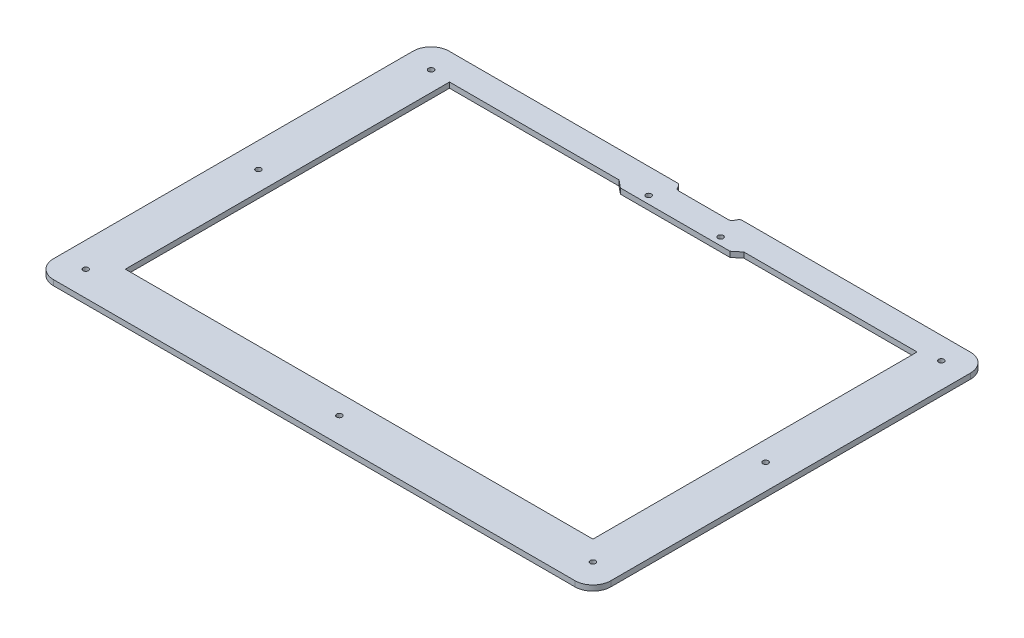
SolidWorks part; units mm, degrees
ref_plane "前视基准面" through (0, 0, 0) normal (0, 0, 1) x (1, 0, 0)
ref_plane "上视基准面" through (0, 0, 0) normal (0, 1, 0) x (1, 0, 0)
ref_plane "右视基准面" through (0, 0, 0) normal (1, 0, 0) x (0, 0, -1)
sketch "草图1" plane through (0, 0, 0) normal (0, 1, 0) x (1, 0, 0)
  line L0 (184.4552, -18.25) -> (188.75, -14.75)
  line L1 (10, 0) -> (136.8844, 0)
  line L2 (0, -10) -> (0, -210)
  line L3 (10, -220) -> (300, -220)
  line L4 (310, -10) -> (310, -210)
  line L5 (28.75, -14.75) -> (47.25, -14.75) construction
  line L6 (28.75, -14.75) -> (28.75, -33.25) construction
  line L7 (28.75, -33.25) -> (47.25, -33.25) construction
  line L8 (173, -85) -> (173, 0) construction
  line L9 (173, -85) -> (310, -85) construction
  line L10 (190, -66) -> (190, 0) construction
  line L11 (215, -58) -> (215, 0) construction
  line L12 (241, -58) -> (241, 0) construction
  line L13 (247, -84) -> (247, 0) construction
  line L14 (222, -84) -> (222, 0) construction
  line L15 (0, -220) -> (310, 0) construction
  line L16 (241, -58) -> (310, -58) construction
  line L17 (247, -84) -> (310, -84) construction
  line L18 (215, -58) -> (310, -58) construction
  line L19 (222, -84) -> (310, -84) construction
  line L20 (190, -66) -> (310, -66) construction
  line L21 (310, -220) -> (0, 0) construction
  line L23 (139.4291, -2.4682) -> (138.6344, -1.0318)
  line L24 (170.5709, -2.4682) -> (171.3656, -1.0318)
  line L25 (173.1156, 0) -> (300, 0)
  line L26 (155, -110) -> (155, -220) construction
  line L27 (47.25, -14.75) -> (47.25, -33.25) construction
  line L28 (28.75, -14.75) -> (47.25, -33.25) construction
  line L29 (28.75, -33.25) -> (47.25, -14.75) construction
  line L30 (52.75, -14.75) -> (71.25, -14.75) construction
  line L31 (52.75, -14.75) -> (52.75, -33.25) construction
  line L32 (52.75, -33.25) -> (71.25, -33.25) construction
  line L33 (71.25, -14.75) -> (71.25, -33.25) construction
  line L34 (52.75, -14.75) -> (71.25, -33.25) construction
  line L35 (52.75, -33.25) -> (71.25, -14.75) construction
  line L36 (76.75, -14.75) -> (95.25, -14.75) construction
  line L37 (76.75, -14.75) -> (76.75, -33.25) construction
  line L38 (76.75, -33.25) -> (95.25, -33.25) construction
  line L39 (95.25, -14.75) -> (95.25, -33.25) construction
  line L40 (76.75, -14.75) -> (95.25, -33.25) construction
  line L41 (76.75, -33.25) -> (95.25, -14.75) construction
  line L42 (100.75, -14.75) -> (119.25, -14.75) construction
  line L43 (100.75, -14.75) -> (100.75, -33.25) construction
  line L44 (100.75, -33.25) -> (119.25, -33.25) construction
  line L45 (119.25, -14.75) -> (119.25, -33.25) construction
  line L46 (100.75, -14.75) -> (119.25, -33.25) construction
  line L47 (100.75, -33.25) -> (119.25, -14.75) construction
  line L48 (188.75, -14.75) -> (207.25, -14.75) construction
  line L49 (188.75, -14.75) -> (188.75, -33.25) construction
  line L50 (188.75, -33.25) -> (207.25, -33.25) construction
  line L51 (207.25, -14.75) -> (207.25, -33.25) construction
  line L52 (188.75, -14.75) -> (207.25, -33.25) construction
  line L53 (188.75, -33.25) -> (207.25, -14.75) construction
  line L54 (212.75, -14.75) -> (231.25, -14.75) construction
  line L55 (212.75, -14.75) -> (212.75, -33.25) construction
  line L56 (212.75, -33.25) -> (231.25, -33.25) construction
  line L57 (231.25, -14.75) -> (231.25, -33.25) construction
  line L58 (212.75, -14.75) -> (231.25, -33.25) construction
  line L59 (212.75, -33.25) -> (231.25, -14.75) construction
  line L60 (236.75, -14.75) -> (255.25, -14.75) construction
  line L61 (236.75, -14.75) -> (236.75, -33.25) construction
  line L62 (236.75, -33.25) -> (255.25, -33.25) construction
  line L63 (255.25, -14.75) -> (255.25, -33.25) construction
  line L64 (236.75, -14.75) -> (255.25, -33.25) construction
  line L65 (236.75, -33.25) -> (255.25, -14.75) construction
  line L66 (260.75, -14.75) -> (279.25, -14.75) construction
  line L67 (260.75, -14.75) -> (260.75, -33.25) construction
  line L68 (260.75, -33.25) -> (279.25, -33.25) construction
  line L69 (279.25, -14.75) -> (279.25, -33.25) construction
  line L70 (260.75, -14.75) -> (279.25, -33.25) construction
  line L71 (260.75, -33.25) -> (279.25, -14.75) construction
  line L73 (123.5448, -18.25) -> (141.1791, -18.25)
  line L74 (141.1791, -18.25) -> (141.1791, -3.5) construction
  line L75 (119.25, -14.75) -> (25, -14.75)
  line L76 (25, -14.75) -> (25, -195)
  line L77 (25, -195) -> (285, -195)
  line L79 (285, -195) -> (285, -14.75)
  line L80 (188.75, -14.75) -> (285, -14.75)
  line L81 (184.4552, -18.25) -> (168.8209, -18.25)
  line L82 (168.8209, -3.5) -> (168.8209, -18.25) construction
  line L83 (123.5448, -18.25) -> (119.25, -14.75)
  line L84 (141.1791, -3.5) -> (168.8209, -3.5)
  line L85 (141.1791, -18.25) -> (168.8209, -18.25)
  arc A0 (10, 0) -> (0, -10) centre (10, -10) ccw
  arc A1 (0, -210) -> (10, -220) centre (10, -210) ccw
  arc A2 (300, -220) -> (310, -210) centre (300, -210) ccw
  arc A3 (300, 0) -> (310, -10) centre (300, -10) cw
  circle A8 centre (173, -85) radius 11 construction
  circle A9 centre (190, -66) radius 11 construction
  circle A11 centre (215, -58) radius 11 construction
  circle A12 centre (222, -84) radius 11 construction
  circle A13 centre (247, -84) radius 11 construction
  circle A14 centre (241, -58) radius 11 construction
  circle A15 centre (14, -14) radius 1.5
  circle A16 centre (14, -206) radius 1.5
  circle A17 centre (296, -206) radius 1.5
  circle A18 centre (296, -12.2857) radius 1.5
  arc A19 (173.1156, 0) -> (171.3656, -1.0318) centre (173.1156, -2) ccw
  arc A20 (170.5709, -2.4682) -> (168.8209, -3.5) centre (168.8209, -1.5) cw
  arc A21 (141.1791, -3.5) -> (139.4291, -2.4682) centre (141.1791, -1.5) cw
  arc A22 (136.8844, 0) -> (138.6344, -1.0318) centre (136.8844, -2) cw
  circle A24 centre (198, -90) radius 11 construction
  circle A25 centre (114, -130) radius 13.5 construction
  circle A26 centre (190, -130) radius 13.5 construction
  circle A27 centre (155, -206) radius 1.5
  circle A28 centre (175, -14) radius 1.5
  circle A29 centre (145, -138) radius 11 construction
  circle A30 centre (106, -90) radius 11 construction
  circle A31 centre (84, -77) radius 11 construction
  circle A32 centre (58, -80) radius 11 construction
  circle A33 centre (36, -97) radius 11 construction
  circle A34 centre (89, -53) radius 11 construction
  circle A35 centre (266, -66) radius 11 construction
  circle A36 centre (110, -24) radius 4.5 construction
  circle A37 centre (86, -24) radius 4.5 construction
  circle A38 centre (62, -24) radius 4.5 construction
  circle A39 centre (38, -24) radius 4.5 construction
  circle A40 centre (198, -24) radius 4.5 construction
  circle A41 centre (222, -24) radius 4.5 construction
  circle A42 centre (246, -24) radius 4.5 construction
  circle A43 centre (270, -24) radius 4.5 construction
  circle A48 centre (135, -14) radius 1.5
  circle A51 centre (296, -110) radius 1.5
  circle A52 centre (14, -110) radius 1.5
  point P8 (0, 0)
  point P12 (0, -220)
  point P15 (310, -220)
  point P18 (310, 0)
  point P70 (171.9365, 0)
  point P73 (170, -3.5)
  point P76 (140, -3.5)
  point P79 (138.0635, 0)
  dimension "D3" = 10
  dimension "D7" = 90
  dimension "D10" = 22
  dimension "D15" = 53
  dimension "D16" = 22
  dimension "D19" = 22
  dimension "D20" = 22
  dimension "D21" = 22
  dimension "D22" = 84
  dimension "D23" = 22
  dimension "D24" = 22
  dimension "D32" = 22
  dimension "D34" = 3
  dimension "D37" = 3
  dimension "D40" = 3
  dimension "D43" = 3
  dimension "D47" = 3.5
  dimension "D50" = 140
  dimension "D51" = 2
  dimension "D52" = 90
  dimension "D54" = 27
  dimension "D56" = 27
  dimension "D59" = 3
  dimension "D61" = 14
  dimension "D62" = 3
  dimension "D64" = 22
  dimension "D8" = 22
  dimension "D9" = 22
  dimension "D11" = 22
  dimension "D12" = 22
  dimension "D13" = 22
  dimension "D76" = 9
  dimension "D84" = 9
  dimension "D86" = 3
  dimension "D89" = 18.5
  dimension "D92" = 18.5
  dimension "D95" = 18.5
  dimension "D98" = 3
  dimension "D101" = 18.5
  dimension "D103" = 18.5
  dimension "D87" = 3
  dimension "D109" = 14.75
  dimension "D118" = 4.2948
  dimension "D120" = 4.2948
  dimension "D119" = 1.75
  dimension "D1" = 220
  dimension "D2" = 310
  dimension "D14" = 89
  dimension "D17" = 85
  dimension "D18" = 137
  dimension "D25" = 66
  dimension "D26" = 120
  dimension "D27" = 36
  dimension "D28" = 58
  dimension "D29" = 95
  dimension "D30" = 88
  dimension "D31" = 69
  dimension "D33" = 63
  dimension "D35" = 14
  dimension "D36" = 14
  dimension "D38" = 14
  dimension "D39" = 14
  dimension "D41" = 14
  dimension "D42" = 14
  dimension "D44" = 14
  dimension "D45" = 12.2857
  dimension "D46" = 4
  dimension "D48" = 30
  dimension "D49" = 4
  dimension "D53" = 112
  dimension "D55" = 114
  dimension "D57" = 90
  dimension "D58" = 120
  dimension "D60" = 14
  dimension "D63" = 135
  dimension "D65" = 82
  dimension "D66" = 145
  dimension "D67" = 97
  dimension "D68" = 80
  dimension "D69" = 58
  dimension "D70" = 84
  dimension "D71" = 77
  dimension "D72" = 90
  dimension "D73" = 106
  dimension "D74" = 44
  dimension "D75" = 66
  dimension "D78" = 24
  dimension "D79" = 110
  dimension "D80" = 24
  dimension "D82" = 24
  dimension "D83" = 24
  dimension "D85" = 40
  dimension "D88" = 18.5
  dimension "D90" = 18.5
  dimension "D91" = 18.5
  dimension "D93" = 18.5
  dimension "D94" = 18.5
  dimension "D96" = 18.5
  dimension "D97" = 18.5
  dimension "D99" = 14
  dimension "D100" = 135
  dimension "D102" = 18.5
  dimension "D104" = 18.5
  dimension "D105" = 18.5
  dimension "D106" = 18.5
  dimension "D107" = 25
  dimension "D108" = 25
  dimension "D110" = 14.75
  dimension "D111" = 17.6344
  dimension "D112" = 15.6344
  dimension "D113" = 94.25
  dimension "D114" = 141.1791
  dimension "D115" = 141.1791
  dimension "D116" = 18.25
  dimension "D117" = 18.25
  dimension "D77" = 4
  dimension "D81" = 4
extrude "凸台-拉伸1" add sketch "草图1" along normal blind 3
